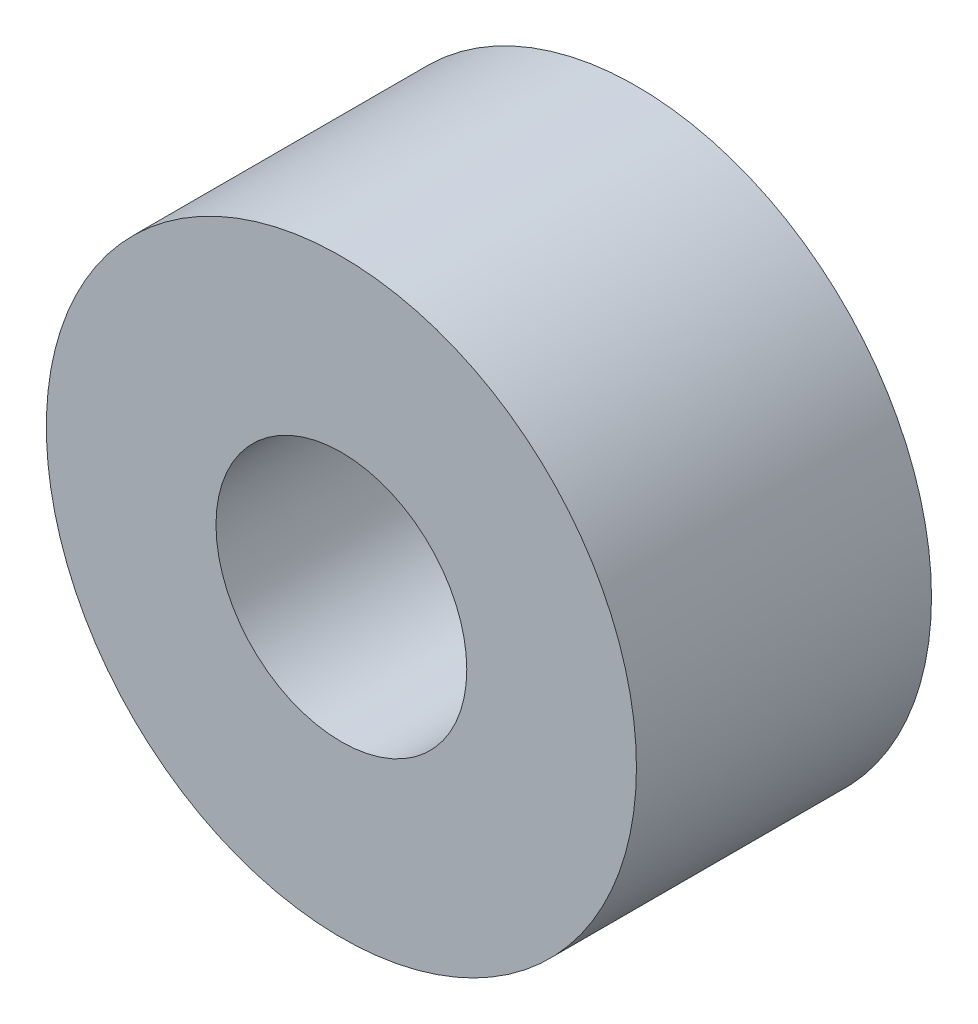
SolidWorks part; units mm, degrees
ref_plane "Front Plane" through (0, 0, 0) normal (0, 0, 1) x (1, 0, 0)
ref_plane "Top Plane" through (0, 0, 0) normal (0, 1, 0) x (1, 0, 0)
ref_plane "Right Plane" through (0, 0, 0) normal (1, 0, 0) x (0, 0, -1)
sketch "Sketch1" plane through (0, 0, 0) normal (0, 0, 1) x (1, 0, 0)
  circle A0 centre (-19.5, 52.8) radius 1.7
  circle A1 centre (-19.5, 52.8) radius 4
extrude "Boss-Extrude1" add sketch "Sketch1" along normal blind 4
